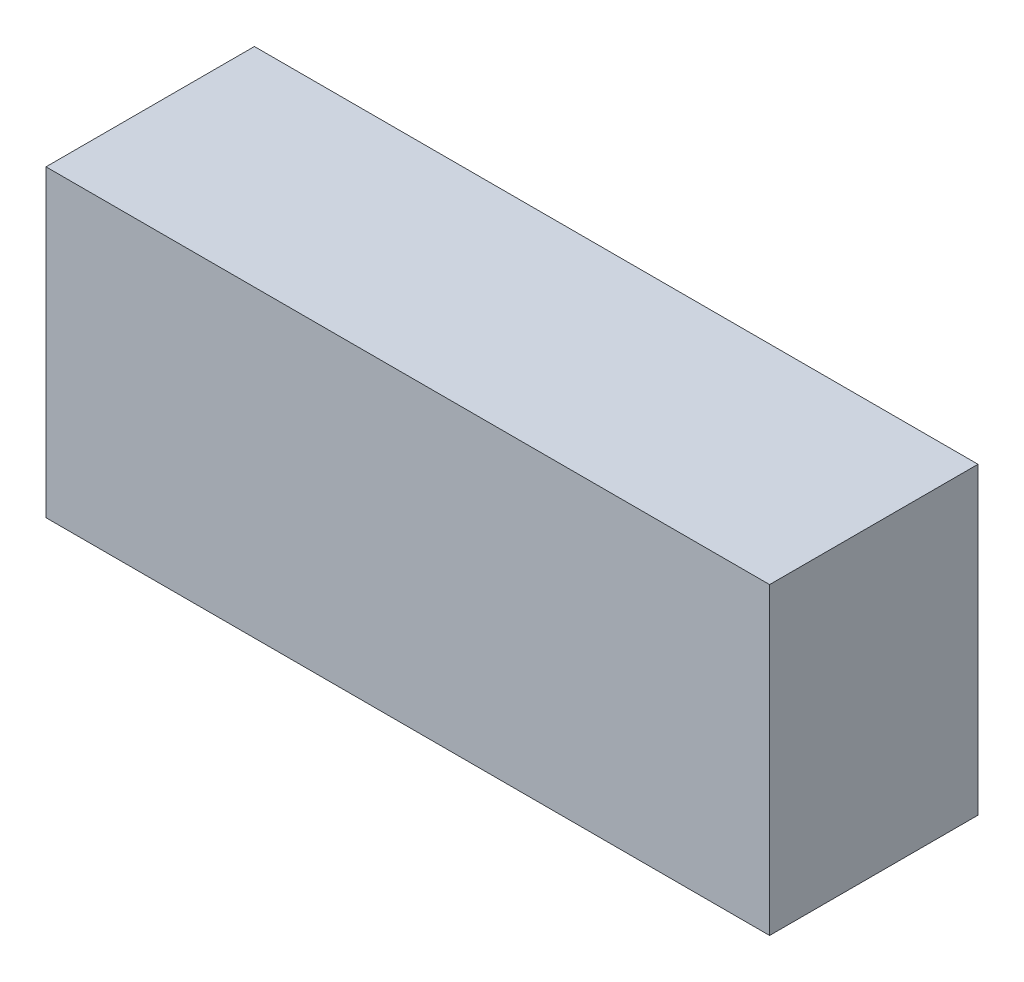
SolidWorks part; units mm, degrees
ref_plane "Front Plane" through (0, 0, 0) normal (0, 0, 1) x (1, 0, 0)
ref_plane "Top Plane" through (0, 0, 0) normal (0, 1, 0) x (1, 0, 0)
ref_plane "Right Plane" through (0, 0, 0) normal (1, 0, 0) x (0, 0, -1)
sketch "Sketch1" plane through (0, 0, 0) normal (0, 0, 1) x (1, 0, 0)
  line L1 (-37.5, 15.75) -> (37.5, 15.75)
  line L2 (-37.5, 15.75) -> (-37.5, -15.75)
  line L3 (-37.5, -15.75) -> (37.5, -15.75)
  line L4 (37.5, 15.75) -> (37.5, -15.75)
  line L5 (-37.5, 15.75) -> (37.5, -15.75) construction
  line L6 (-37.5, -15.75) -> (37.5, 15.75) construction
  point P0 (0, 0)
  dimension "D1" = 75
  dimension "D2" = 31.5
extrude "Boss-Extrude1" add sketch "Sketch1" along normal blind 21.6
